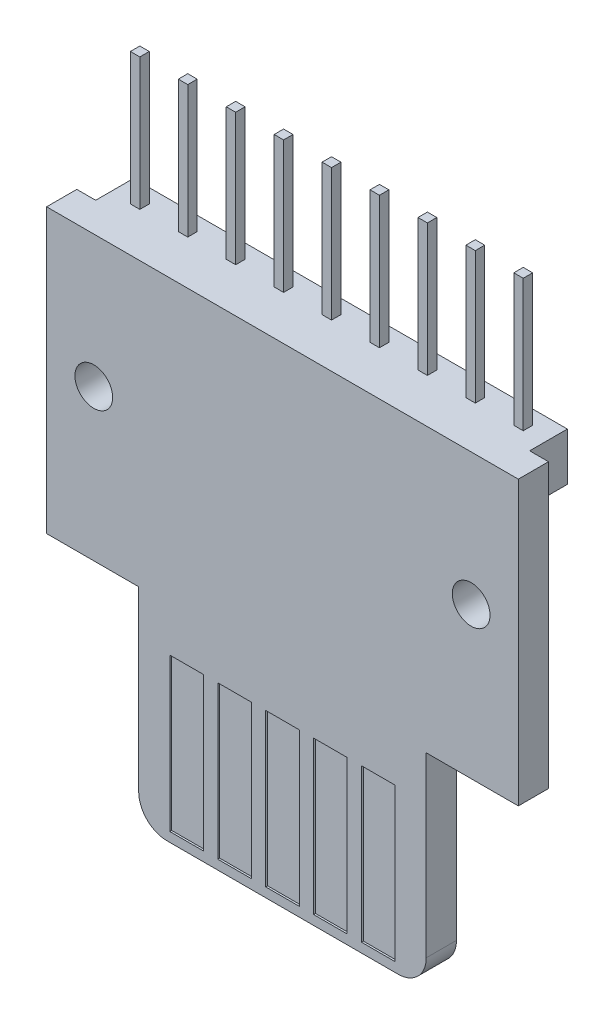
SolidWorks part; units mm, degrees
ref_plane "前视基准面" through (0, 0, 0) normal (0, 0, 1) x (1, 0, 0)
ref_plane "上视基准面" through (0, 0, 0) normal (0, 1, 0) x (1, 0, 0)
ref_plane "右视基准面" through (0, 0, 0) normal (1, 0, 0) x (0, 0, -1)
other "Configuration Table"
sketch "草图1" plane through (0, 0, 0) normal (0, 0, 1) x (1, 0, 0)
  line L0 (-280.0431, 0) -> (-7.62, 0) construction
  line L1 (-12.5, 0) -> (-7.62, 0)
  line L2 (12.5, 0) -> (12.5, 15)
  line L3 (12.5, 15) -> (-12.5, 15)
  line L4 (-12.5, 15) -> (-12.5, 0)
  line L5 (7.62, 0) -> (7.62, -9.41)
  line L6 (6.12, -10.91) -> (-6.12, -10.91)
  line L7 (-7.62, -9.41) -> (-7.62, 0)
  line L8 (7.62, 0) -> (13722.1137, 0) construction
  line L9 (7.62, 0) -> (12.5, 0)
  arc A0 (6.12, -10.91) -> (7.62, -9.41) centre (6.12, -9.41) ccw
  arc A1 (-7.62, -9.41) -> (-6.12, -10.91) centre (-6.12, -9.41) ccw
  circle A2 centre (-10, 8) radius 1
  circle A3 centre (10, 8) radius 1
  point P6 (0, 0)
  dimension "D6" = 3
  dimension "D5" = 3
  dimension "D7" = 10.91
  dimension "D8" = 2
  dimension "D12" = 2
  dimension "D1" = 25
  dimension "D2" = 15
  dimension "D3" = 15.24
  dimension "D4" = 4.88
  dimension "D9" = 8
  dimension "D10" = 2.5
  dimension "D11" = 12.5
  dimension "D13" = 8
  dimension "D14" = 2.5
extrude "凸台-拉伸1" add sketch "草图1" along normal blind 1.6
sketch "草图2" plane through (0, 0, 0) normal (0, 0, 1) x (1, 0, 0)
  line L0 (-6.12, -10.91) -> (6.12, -10.91) construction
  line L1 (-0.89, -2.31) -> (0.89, -2.31)
  line L2 (-0.89, -2.31) -> (-0.89, -10.41)
  line L3 (-0.89, -10.41) -> (0.89, -10.41)
  line L4 (0.89, -2.31) -> (0.89, -10.41)
  line L5 (1.65, -2.31) -> (3.43, -2.31)
  line L6 (1.65, -2.31) -> (1.65, -10.41)
  line L7 (1.65, -10.41) -> (3.43, -10.41)
  line L8 (3.43, -2.31) -> (3.43, -10.41)
  line L9 (4.19, -2.31) -> (5.97, -2.31)
  line L10 (4.19, -2.31) -> (4.19, -10.41)
  line L11 (4.19, -10.41) -> (5.97, -10.41)
  line L12 (5.97, -2.31) -> (5.97, -10.41)
  line L13 (-0.89, -2.31) -> (1.65, -2.31) construction
  line L14 (-3.43, -2.31) -> (-1.65, -2.31)
  line L15 (-3.43, -2.31) -> (-3.43, -10.41)
  line L16 (-3.43, -10.41) -> (-1.65, -10.41)
  line L17 (-1.65, -2.31) -> (-1.65, -10.41)
  line L18 (-5.97, -2.31) -> (-4.19, -2.31)
  line L19 (-5.97, -2.31) -> (-5.97, -10.41)
  line L20 (-5.97, -10.41) -> (-4.19, -10.41)
  line L21 (-4.19, -2.31) -> (-4.19, -10.41)
  line L22 (-0.89, -2.31) -> (-3.43, -2.31) construction
  point P6 (0, -2.31)
  dimension "D1" = 1.78
  dimension "D2" = 8.1
  dimension "D3" = 0.5
  dimension "D5" = 2.54
  dimension "D7" = 2.54
  dimension "D4" = 3
  dimension "D6" = 3
extrude "切除-拉伸1" cut sketch "草图2" along normal blind 0.1
sketch "草图3" plane through (0, 0, 0) normal (0, 0, 1) x (1, 0, 0)
  line L4 (3.43, -2.31) -> (1.65, -2.31)
  line L5 (3.43, -10.41) -> (3.43, -2.31)
  line L6 (1.65, -10.41) -> (3.43, -10.41)
  line L7 (1.65, -2.31) -> (1.65, -10.41)
  line L8 (3.43, -2.31) -> (1.65, -2.31)
  line L9 (3.43, -10.41) -> (3.43, -2.31)
  line L10 (1.65, -10.41) -> (3.43, -10.41)
  line L11 (1.65, -2.31) -> (1.65, -10.41)
  line L12 (0.89, -2.31) -> (-0.89, -2.31)
  line L13 (0.89, -10.41) -> (0.89, -2.31)
  line L14 (-0.89, -10.41) -> (0.89, -10.41)
  line L15 (-0.89, -2.31) -> (-0.89, -10.41)
  line L16 (0.89, -2.31) -> (-0.89, -2.31)
  line L17 (0.89, -10.41) -> (0.89, -2.31)
  line L18 (-0.89, -10.41) -> (0.89, -10.41)
  line L19 (-0.89, -2.31) -> (-0.89, -10.41)
  line L20 (-4.19, -2.31) -> (-5.97, -2.31)
  line L21 (-4.19, -10.41) -> (-4.19, -2.31)
  line L22 (-5.97, -10.41) -> (-4.19, -10.41)
  line L23 (-5.97, -2.31) -> (-5.97, -10.41)
  line L24 (-4.19, -2.31) -> (-5.97, -2.31)
  line L25 (-4.19, -10.41) -> (-4.19, -2.31)
  line L26 (-5.97, -10.41) -> (-4.19, -10.41)
  line L27 (-5.97, -2.31) -> (-5.97, -10.41)
  line L28 (-1.65, -2.31) -> (-3.43, -2.31)
  line L29 (-1.65, -10.41) -> (-1.65, -2.31)
  line L30 (-3.43, -10.41) -> (-1.65, -10.41)
  line L31 (-3.43, -2.31) -> (-3.43, -10.41)
  line L32 (-1.65, -2.31) -> (-3.43, -2.31)
  line L33 (-1.65, -10.41) -> (-1.65, -2.31)
  line L34 (-3.43, -10.41) -> (-1.65, -10.41)
  line L35 (-3.43, -2.31) -> (-3.43, -10.41)
  line L36 (5.97, -2.31) -> (4.19, -2.31)
  line L37 (4.19, -2.31) -> (4.19, -10.41)
  line L38 (4.19, -10.41) -> (5.97, -10.41)
  line L39 (5.97, -10.41) -> (5.97, -2.31)
  line L40 (5.97, -2.31) -> (4.19, -2.31)
  line L41 (4.19, -2.31) -> (4.19, -10.41)
  line L42 (4.19, -10.41) -> (5.97, -10.41)
  line L43 (5.97, -10.41) -> (5.97, -2.31)
  dimension "D1" = 0
  dimension "D2" = 0
  dimension "D3" = 0
  dimension "D4" = 0
  dimension "D5" = 0
extrude "切除-拉伸2" cut sketch "草图3" against normal blind 0.1 from surface at 1.6 starting at face at (-9, 8, 1.6)
sketch "草图4" plane through (0, 0, 0) normal (0, 0, 1) x (1, 0, 0)
  line L0 (12.5, 15) -> (-12.5, 15) construction
  line L1 (-11.5, 15) -> (11.5, 15)
  line L2 (-11.5, 15) -> (-11.5, 12.46)
  line L3 (-11.5, 12.46) -> (11.5, 12.46)
  line L4 (11.5, 15) -> (11.5, 12.46)
  point P6 (0, 15)
  point P7 (0, 15)
  dimension "D1" = 2.54
  dimension "D2" = 23
extrude "凸台-拉伸2" add sketch "草图4" against normal blind 2
sketch "草图5" plane through (0, 0, 0) normal (0, 1, 0) x (1, 0, 0)
  line L0 (2.29, 1.25) -> (2.79, 1.25)
  line L1 (-11.5, 2) -> (11.5, 2) construction
  line L2 (-11.5, 2) -> (-11.5, 0) construction
  line L3 (-11.5, 0) -> (11.5, 0) construction
  line L4 (11.5, 2) -> (11.5, 0) construction
  line L5 (-0.25, 1.25) -> (0.25, 1.25)
  line L6 (-0.25, 1.25) -> (-0.25, 0.75)
  line L7 (-0.25, 0.75) -> (0.25, 0.75)
  line L8 (0.25, 1.25) -> (0.25, 0.75)
  line L9 (-0.25, 1.25) -> (0.25, 0.75) construction
  line L10 (-0.25, 0.75) -> (0.25, 1.25) construction
  line L11 (2.29, 1.25) -> (2.29, 0.75)
  line L12 (2.29, 0.75) -> (2.79, 0.75)
  line L13 (2.79, 1.25) -> (2.79, 0.75)
  line L14 (2.29, 1.25) -> (2.79, 0.75) construction
  line L15 (2.29, 0.75) -> (2.79, 1.25) construction
  line L16 (4.83, 1.25) -> (5.33, 1.25)
  line L17 (4.83, 1.25) -> (4.83, 0.75)
  line L18 (4.83, 0.75) -> (5.33, 0.75)
  line L19 (5.33, 1.25) -> (5.33, 0.75)
  line L20 (4.83, 1.25) -> (5.33, 0.75) construction
  line L21 (4.83, 0.75) -> (5.33, 1.25) construction
  line L22 (7.37, 1.25) -> (7.87, 1.25)
  line L23 (7.37, 1.25) -> (7.37, 0.75)
  line L24 (7.37, 0.75) -> (7.87, 0.75)
  line L25 (7.87, 1.25) -> (7.87, 0.75)
  line L26 (7.37, 1.25) -> (7.87, 0.75) construction
  line L27 (7.37, 0.75) -> (7.87, 1.25) construction
  line L28 (9.91, 1.25) -> (10.41, 1.25)
  line L29 (9.91, 1.25) -> (9.91, 0.75)
  line L30 (9.91, 0.75) -> (10.41, 0.75)
  line L31 (10.41, 1.25) -> (10.41, 0.75)
  line L32 (9.91, 1.25) -> (10.41, 0.75) construction
  line L33 (9.91, 0.75) -> (10.41, 1.25) construction
  line L34 (0, 1) -> (2.54, 1) construction
  line L35 (-2.79, 1.25) -> (-2.29, 1.25)
  line L36 (-2.79, 1.25) -> (-2.79, 0.75)
  line L37 (-2.79, 0.75) -> (-2.29, 0.75)
  line L38 (-2.29, 1.25) -> (-2.29, 0.75)
  line L39 (-2.79, 1.25) -> (-2.29, 0.75) construction
  line L40 (-2.79, 0.75) -> (-2.29, 1.25) construction
  line L41 (-2.54, 1) -> (0, 1) construction
  line L42 (-5.33, 1.25) -> (-4.83, 1.25)
  line L43 (-5.33, 1.25) -> (-5.33, 0.75)
  line L44 (-5.33, 0.75) -> (-4.83, 0.75)
  line L45 (-4.83, 1.25) -> (-4.83, 0.75)
  line L46 (-5.33, 1.25) -> (-4.83, 0.75) construction
  line L47 (-5.33, 0.75) -> (-4.83, 1.25) construction
  line L48 (-5.08, 1) -> (-2.54, 1) construction
  line L49 (-7.87, 1.25) -> (-7.37, 1.25)
  line L50 (-7.87, 1.25) -> (-7.87, 0.75)
  line L51 (-7.87, 0.75) -> (-7.37, 0.75)
  line L52 (-7.37, 1.25) -> (-7.37, 0.75)
  line L53 (-7.87, 1.25) -> (-7.37, 0.75) construction
  line L54 (-7.87, 0.75) -> (-7.37, 1.25) construction
  line L55 (-7.62, 1) -> (-5.08, 1) construction
  line L56 (-10.41, 1.25) -> (-9.91, 1.25)
  line L57 (-10.41, 1.25) -> (-10.41, 0.75)
  line L58 (-10.41, 0.75) -> (-9.91, 0.75)
  line L59 (-9.91, 1.25) -> (-9.91, 0.75)
  line L60 (-10.41, 1.25) -> (-9.91, 0.75) construction
  line L61 (-10.41, 0.75) -> (-9.91, 1.25) construction
  line L62 (-10.16, 1) -> (-7.62, 1) construction
  line L63 (0, 1) -> (-2.54, 1) construction
  point P6 (0, 1)
  point P14 (2.54, 1)
  point P19 (5.08, 1)
  point P24 (7.62, 1)
  point P29 (10.16, 1)
  point P36 (-2.54, 1)
  point P43 (-5.08, 1)
  point P50 (-7.62, 1)
  point P57 (-10.16, 1)
  dimension "D1" = 0.5
  dimension "D2" = 0.5
  dimension "D3" = 1
  dimension "D5" = 2.54
  dimension "D7" = 2.54
  dimension "D4" = 5
  dimension "D6" = 5
extrude "凸台-拉伸3" add sketch "草图5" along normal blind 7 from surface at 15 starting at face at (0, 15, -0.1)
